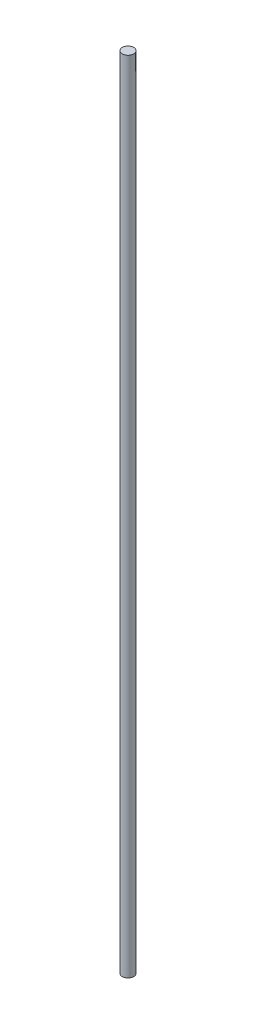
SolidWorks part; units mm, degrees
ref_plane "Front Plane" through (0, 0, 0) normal (0, 0, 1) x (1, 0, 0)
ref_plane "Top Plane" through (0, 0, 0) normal (0, 1, 0) x (1, 0, 0)
ref_plane "Right Plane" through (0, 0, 0) normal (1, 0, 0) x (0, 0, -1)
sketch "Sketch1" plane through (0, 0, 0) normal (0, 1, 0) x (1, 0, 0)
  circle A0 centre (0, 0) radius 6.35
  dimension "D1" = 12.7
extrude "Boss-Extrude1" add sketch "Sketch1" along normal blind 892
